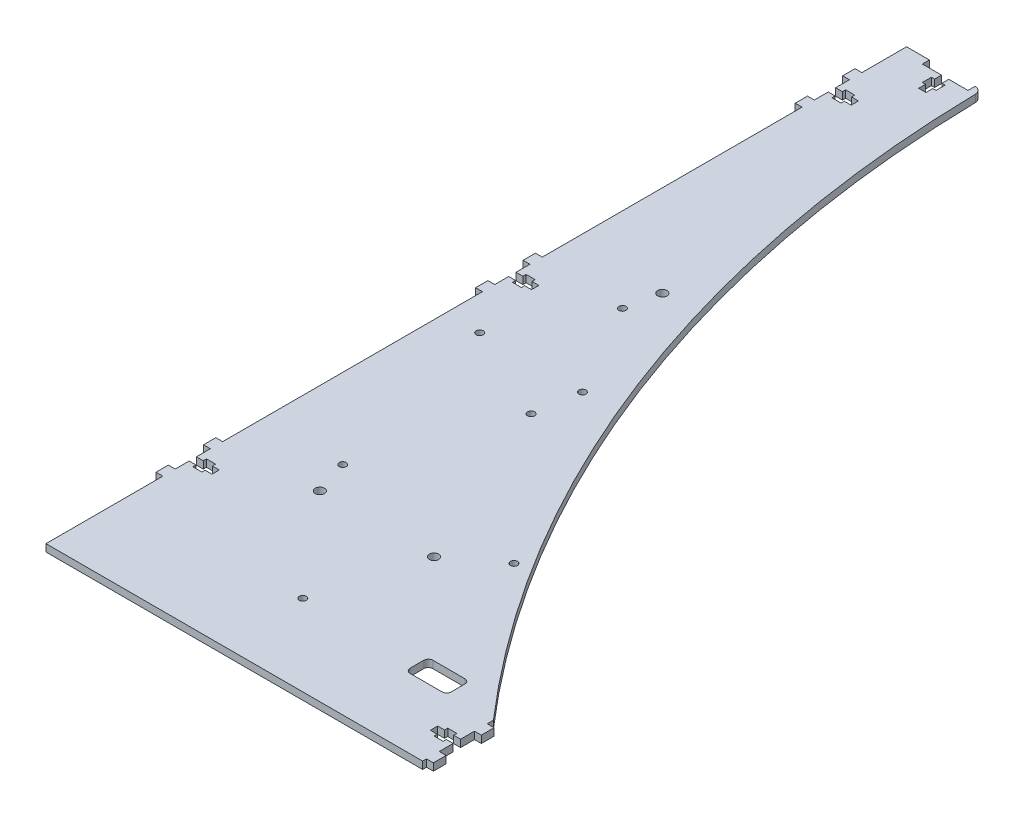
SolidWorks part; units mm, degrees
ref_plane "Alzado" through (0, 0, 0) normal (0, 0, 1) x (1, 0, 0)
ref_plane "Planta" through (0, 0, 0) normal (0, 1, 0) x (1, 0, 0)
ref_plane "Vista lateral" through (0, 0, 0) normal (1, 0, 0) x (0, 0, -1)
sketch "Croquis1" plane through (0, 0, 0) normal (0, 1, 0) x (1, 0, 0)
  line L0 (7, 65.9) -> (10, 65.9)
  line L1 (0, 0) -> (165, 0)
  line L2 (0, 0) -> (0, 51)
  line L3 (0, 377) -> (10, 377)
  line L4 (165, 0) -> (165, 1.5)
  line L5 (0, 51) -> (-3, 51)
  line L7 (0, 56.8) -> (-3, 56.8)
  line L8 (-3, 51) -> (-3, 56.8)
  line L9 (0, 71.8) -> (-3, 71.8)
  line L11 (0, 77.6) -> (-3, 77.6)
  line L12 (-3, 71.8) -> (-3, 77.6)
  line L13 (0, 65.9) -> (3, 65.9)
  line L15 (0, 62.7) -> (3, 62.7)
  line L16 (10, 65.9) -> (10, 62.7)
  line L17 (7, 67.3) -> (3, 67.3)
  line L18 (7, 67.3) -> (7, 65.9)
  line L19 (7, 61.3) -> (3, 61.3)
  line L20 (3, 67.3) -> (3, 65.9)
  line L21 (3, 62.7) -> (3, 61.3)
  line L22 (7, 62.7) -> (7, 61.3)
  line L23 (7, 62.7) -> (10, 62.7)
  line L24 (0, 65.9) -> (0, 71.8)
  line L25 (0, 77.6) -> (0, 191)
  line L26 (0, 56.8) -> (0, 62.7)
  line L27 (0, 217.6) -> (-3, 217.6)
  line L28 (-3, 211.8) -> (-3, 217.6)
  line L29 (0, 211.8) -> (-3, 211.8)
  line L30 (0, 205.9) -> (3, 205.9)
  line L31 (3, 207.3) -> (3, 205.9)
  line L32 (7, 207.3) -> (3, 207.3)
  line L33 (7, 207.3) -> (7, 205.9)
  line L34 (7, 205.9) -> (10, 205.9)
  line L35 (10, 205.9) -> (10, 202.7)
  line L36 (7, 202.7) -> (10, 202.7)
  line L37 (7, 202.7) -> (7, 201.3)
  line L38 (7, 201.3) -> (3, 201.3)
  line L39 (3, 202.7) -> (3, 201.3)
  line L40 (0, 202.7) -> (3, 202.7)
  line L41 (0, 196.8) -> (-3, 196.8)
  line L42 (-3, 191) -> (-3, 196.8)
  line L43 (0, 191) -> (-3, 191)
  line L44 (0, 357.6) -> (-3, 357.6)
  line L45 (-3, 351.8) -> (-3, 357.6)
  line L46 (0, 351.8) -> (-3, 351.8)
  line L47 (0, 345.9) -> (3, 345.9)
  line L48 (3, 347.3) -> (3, 345.9)
  line L49 (7, 347.3) -> (3, 347.3)
  line L50 (7, 347.3) -> (7, 345.9)
  line L51 (7, 345.9) -> (10, 345.9)
  line L52 (10, 345.9) -> (10, 342.7)
  line L53 (7, 342.7) -> (10, 342.7)
  line L54 (7, 342.7) -> (7, 341.3)
  line L55 (7, 341.3) -> (3, 341.3)
  line L56 (3, 342.7) -> (3, 341.3)
  line L57 (0, 342.7) -> (3, 342.7)
  line L58 (0, 336.8) -> (-3, 336.8)
  line L59 (-3, 331) -> (-3, 336.8)
  line L60 (0, 331) -> (-3, 331)
  line L61 (0, 357.6) -> (0, 377)
  line L62 (0, 345.9) -> (0, 351.8)
  line L63 (0, 336.8) -> (0, 342.7)
  line L64 (0, 217.6) -> (0, 331)
  line L65 (0, 205.9) -> (0, 211.8)
  line L66 (0, 196.8) -> (0, 202.7)
  line L67 (21.6, 373.9) -> (30, 373.9)
  line L69 (10, 377) -> (10, 373.9)
  line L70 (10, 373.9) -> (18.4, 373.9)
  line L71 (30, 377) -> (30, 373.9)
  line L73 (18.4, 373.9) -> (18.4, 370.9)
  line L74 (18.4, 363.9) -> (21.6, 363.9)
  line L75 (21.6, 373.9) -> (21.6, 370.9)
  line L76 (17, 370.9) -> (18.4, 370.9)
  line L77 (17, 370.9) -> (17, 366.9)
  line L78 (17, 366.9) -> (18.4, 366.9)
  line L79 (23, 370.9) -> (23, 366.9)
  line L80 (21.6, 370.9) -> (23, 370.9)
  line L81 (18.4, 366.9) -> (18.4, 363.9)
  line L82 (21.6, 366.9) -> (21.6, 363.9)
  line L83 (21.6, 366.9) -> (23, 366.9)
  line L84 (30, 377) -> (165, 377)
  line L85 (158, 13.4) -> (158, 12)
  line L86 (165, 1.5) -> (168, 1.5)
  line L88 (165, 7.5) -> (168, 7.5)
  line L89 (168, 1.5) -> (168, 7.5)
  line L90 (165, 22.5) -> (168, 22.5)
  line L92 (165, 28.5) -> (168, 28.5)
  line L93 (168, 22.5) -> (168, 28.5)
  line L94 (165, 16.6) -> (162, 16.6)
  line L96 (165, 13.4) -> (162, 13.4)
  line L97 (155, 16.6) -> (155, 13.4)
  line L98 (158, 18) -> (162, 18)
  line L99 (158, 18) -> (158, 16.6)
  line L100 (158, 12) -> (162, 12)
  line L101 (162, 18) -> (162, 16.6)
  line L102 (158, 16.6) -> (155, 16.6)
  line L103 (162, 13.4) -> (162, 12)
  line L104 (158, 13.4) -> (155, 13.4)
  line L105 (165, 16.6) -> (165, 22.5)
  line L106 (165, 7.5) -> (165, 13.4)
  line L107 (165, 28.5) -> (165, 377)
  dimension "D1" = 377
  dimension "D2" = 165
  dimension "D3" = 3
  dimension "D4" = 5.8
  dimension "D5" = 3
  dimension "D6" = 5.8
  dimension "D7" = 15
  dimension "D8" = 10
  dimension "D9" = 3.2
  dimension "D10" = 5.9
  dimension "D11" = 4
  dimension "D12" = 6
  dimension "D13" = 1.4
  dimension "D14" = 51
  dimension "D15" = 3
  dimension "D17" = 140
  dimension "D18" = 20
  dimension "D19" = 10
  dimension "D20" = 3.1
  dimension "D21" = 10
  dimension "D22" = 3.2
  dimension "D23" = 4
  dimension "D24" = 6
  dimension "D25" = 1.4
  dimension "D26" = 8.4
  dimension "D27" = 3
  dimension "D28" = 6
  dimension "D29" = 6
  dimension "D30" = 3
  dimension "D31" = 3
  dimension "D32" = 3.2
  dimension "D33" = 4
  dimension "D34" = 6
  dimension "D35" = 1.4
  dimension "D36" = 10
  dimension "D37" = 3
  dimension "D38" = 15
  dimension "D39" = 5.9
  dimension "D40" = 1.5
  dimension "D16" = 3
extrude "Saliente-Extruir1" add sketch "Croquis1" along normal blind 3.2
sketch "Croquis2" plane through (0, 0, 0) normal (0, -1, 0) x (1, 0, 0)
  line L0 (30, -377) -> (30, -373.9) construction
  line L1 (165, -377) -> (33, -377)
  line L2 (165, -377) -> (165, -31)
  line L3 (165, -31) -> (33, -31) construction
  line L4 (33, -377) -> (33, -31) construction
  line L5 (168, -28.5) -> (165, -28.5) construction
  arc A0 (33, -377) -> (165, -31) centre (571.7994, -384.3743) cw
  dimension "D1" = 3
  dimension "D2" = 2.5
extrude "Cortar-Extruir1" cut sketch "Croquis2" against normal up to surface (3.2 mm away) up to face at (40.46, 3.2, -192.406)
fillet "Redondeo1" radius 3 1 edges at (33, 1.6, -377)
sketch "Croquis3" plane through (0, 3.2, 0) normal (0, 1, 0) x (1, 0, 0)
  line L0 (0, 202.7) -> (0, 196.8) construction
  line L1 (0, 0) -> (165, 0) construction
  circle A0 centre (40, 80) radius 2.05
  circle A1 centre (90, 80) radius 2.05
  circle A2 centre (40, 230) radius 2.05
  dimension "D1" = 4.1
  dimension "D2" = 50
  dimension "D3" = 150
  dimension "D4" = 40
  dimension "D5" = 80
extrude "Cortar-Extruir2" cut sketch "Croquis3" against normal up to surface (3.2 mm away) up to face at (39.9955, 0, -192.4968)
sketch "Croquis4" plane through (0, 0, 0) normal (0, -1, 0) x (1, 0, 0)
  line L1 (0, 0) -> (165, 0) construction
  line L3 (165, -28.5) -> (165, -31) construction
  line L4 (143, -30.5) -> (129, -30.5)
  line L5 (145, -32.5) -> (145, -38.5)
  line L6 (143, -40.5) -> (129, -40.5)
  line L7 (127, -32.5) -> (127, -38.5)
  arc A14 (143, -30.5) -> (145, -32.5) centre (143, -32.5) cw
  arc A15 (127, -38.5) -> (129, -40.5) centre (129, -38.5) ccw
  arc A16 (127, -32.5) -> (129, -30.5) centre (129, -32.5) cw
  arc A17 (145, -38.5) -> (143, -40.5) centre (143, -38.5) cw
  point P38 (145, -30.5)
  point P41 (127, -40.5)
  point P46 (145, -40.5)
  dimension "D3" = 20
  dimension "D20" = 2
  dimension "D16" = 18
  dimension "D17" = 10
  dimension "D19" = 30.5
extrude "Cortar-Extruir3" cut sketch "Croquis4" against normal up to surface (3.2 mm away) up to face at (40, 3.2, -227.95)
sketch "Croquis5" plane through (0, 0, 0) normal (0, -1, 0) x (1, 0, 0)
  line L0 (0, 0) -> (165, 0) construction
  line L1 (0, -191) -> (0, -77.6) construction
  line L2 (127, -35.5) -> (77, -35.5) construction
  line L3 (127, -32.5) -> (127, -38.5) construction
  circle A0 centre (110, -95) radius 1.55
  circle A1 centre (35, -95) radius 1.55
  circle A2 centre (15, -175) radius 1.55
  circle A3 centre (60, -175) radius 1.55
  circle A4 centre (77, -35.5) radius 1.55
  circle A5 centre (37, -215.5) radius 1.55
  circle A6 centre (57, -155.5) radius 1.55
  dimension "D1" = 3.1
  dimension "D2" = 75
  dimension "D3" = 95
  dimension "D4" = 35
  dimension "D5" = 45
  dimension "D6" = 15
  dimension "D7" = 80
  dimension "D8" = 50
  dimension "D9" = 180
  dimension "D10" = 40
  dimension "D11" = 120
  dimension "D12" = 20
extrude "Cortar-Extruir4" cut sketch "Croquis5" against normal up to surface (3.2 mm away) up to face at (136, 3.2, -35.5)
sketch "Croquis6" plane through (0, 0, 0) normal (0, -1, 0) x (1, 0, 0)
  line L0 (165, -28.5) -> (165, -31) construction
  line L1 (-3, -357.6) -> (0, -357.6)
  line L2 (-3, -357.6) -> (-3, -357.4)
  line L3 (-3, -357.4) -> (0, -357.4)
  line L4 (0, -357.6) -> (0, -357.4)
  line L5 (-3, -351.8) -> (0, -351.8)
  line L6 (-3, -351.8) -> (-3, -352)
  line L7 (-3, -352) -> (0, -352)
  line L8 (0, -351.8) -> (0, -352)
  line L9 (-3, -336.8) -> (0, -336.8)
  line L10 (-3, -336.8) -> (-3, -336.6)
  line L11 (-3, -336.6) -> (0, -336.6)
  line L12 (0, -336.8) -> (0, -336.6)
  line L13 (-3, -331) -> (0, -331)
  line L14 (-3, -331) -> (-3, -331.2)
  line L15 (-3, -331.2) -> (0, -331.2)
  line L16 (0, -331) -> (0, -331.2)
  line L17 (-3, -217.6) -> (0, -217.6)
  line L18 (-3, -217.6) -> (-3, -217.4)
  line L19 (-3, -217.4) -> (0, -217.4)
  line L20 (0, -217.6) -> (0, -217.4)
  line L21 (-3, -211.8) -> (0, -211.8)
  line L22 (-3, -211.8) -> (-3, -212)
  line L23 (-3, -212) -> (0, -212)
  line L24 (0, -211.8) -> (0, -212)
  line L25 (-3, -196.8) -> (0, -196.8)
  line L26 (-3, -196.8) -> (-3, -196.6)
  line L27 (-3, -196.6) -> (0, -196.6)
  line L28 (0, -196.8) -> (0, -196.6)
  line L29 (-3, -191) -> (0, -191)
  line L30 (-3, -191) -> (-3, -191.2)
  line L31 (-3, -191.2) -> (0, -191.2)
  line L32 (0, -191) -> (0, -191.2)
  line L33 (-3, -77.6) -> (0, -77.6)
  line L34 (-3, -77.6) -> (-3, -77.4)
  line L35 (-3, -77.4) -> (0, -77.4)
  line L36 (0, -77.6) -> (0, -77.4)
  line L37 (-3, -71.8) -> (0, -71.8)
  line L38 (-3, -71.8) -> (-3, -72)
  line L39 (-3, -72) -> (0, -72)
  line L40 (0, -71.8) -> (0, -72)
  line L41 (-3, -56.8) -> (0, -56.8)
  line L42 (-3, -56.8) -> (-3, -56.6)
  line L43 (-3, -56.6) -> (0, -56.6)
  line L44 (0, -56.8) -> (0, -56.6)
  line L45 (-3, -51) -> (0, -51)
  line L46 (-3, -51) -> (-3, -51.2)
  line L47 (-3, -51.2) -> (0, -51.2)
  line L48 (0, -51) -> (0, -51.2)
  line L49 (168, -28.5) -> (165, -28.5)
  line L50 (168, -28.5) -> (168, -28.3)
  line L51 (168, -28.3) -> (165, -28.3)
  line L52 (165, -28.5) -> (165, -28.3)
  line L54 (168, -22.5) -> (165, -22.5)
  line L55 (168, -22.5) -> (168, -22.7)
  line L56 (168, -22.7) -> (165, -22.7)
  line L57 (165, -22.5) -> (165, -22.7)
  line L58 (168, -7.5) -> (165, -7.5)
  line L59 (168, -7.5) -> (168, -7.3)
  line L60 (168, -7.3) -> (165, -7.3)
  line L61 (165, -7.5) -> (165, -7.3)
  line L62 (168, -1.5) -> (165, -1.5)
  line L63 (168, -1.5) -> (168, -1.7)
  line L64 (168, -1.7) -> (165, -1.7)
  line L65 (165, -1.5) -> (165, -1.7)
  dimension "D1" = 0.2
  dimension "D2" = 0.2
  dimension "D3" = 0.2
  dimension "D4" = 0.2
  dimension "D5" = 0.2
  dimension "D6" = 0.2
  dimension "D7" = 0.2
  dimension "D8" = 0.2
  dimension "D9" = 0.2
  dimension "D10" = 0.2
  dimension "D11" = 0.2
  dimension "D12" = 0.2
  dimension "D13" = 0.2
  dimension "D14" = 0.2
  dimension "D15" = 0.2
  dimension "D16" = 0.2
extrude "Cortar-Extruir5" cut sketch "Croquis6" against normal up to surface (3.2 mm away) up to face at (110, 3.2, -93.45)
